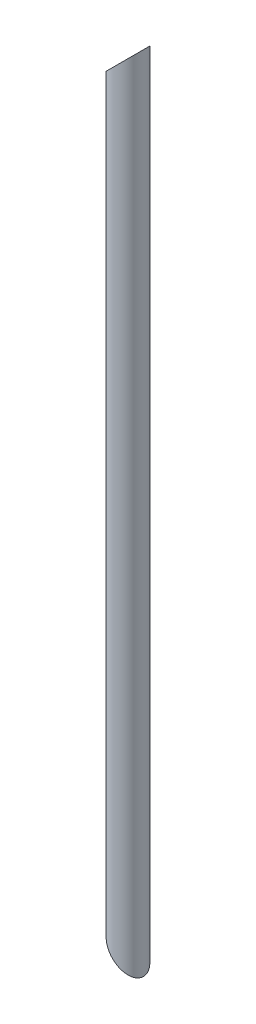
SolidWorks part; units mm, degrees
ref_plane "Plano frontal" through (0, 0, 0) normal (0, 0, 1) x (1, 0, 0)
ref_plane "Plano superior" through (0, 0, 0) normal (0, 1, 0) x (1, 0, 0)
ref_plane "Plano direito" through (0, 0, 0) normal (1, 0, 0) x (0, 0, -1)
sketch "Esboço2" plane through (0, 0, 0) normal (0, 0, 1) x (1, 0, 0)
  line L0 (0, 0) -> (0, 1650) construction
  line L1 (31.75, 0) -> (31.75, 1650)
  line L2 (31.75, 1650) -> (0, 1650)
  line L3 (31.75, 0) -> (0, 0)
  line L4 (0, 0) -> (0, 1650)
  dimension "D1" = 31.75
  dimension "D2" = 1650
revolve "Revolução2" add sketch "Esboço2" angle 360 about L0
sketch "Esboço3" plane through (0, 0, 0) normal (0, 0, 1) x (1, 0, 0)
  line L0 (-31.75, 1650) -> (31.75, 1650)
  line L1 (31.75, 1650) -> (-31.75, 1586.5)
  line L2 (-31.75, 1650) -> (-31.75, 0) construction
  line L3 (-31.75, 1586.5) -> (-31.75, 1650)
  line L4 (31.75, 0) -> (-31.75, 63.5)
  line L8 (-31.75, 63.5) -> (-31.75, 0)
  line L9 (-31.75, 0) -> (31.75, 0)
extrude "Corte-extrusão1" cut sketch "Esboço3" against normal through all both and the other way through all
sketch "Esboço9" plane through (0, 0, 0) normal (0, 1, 0) x (1, 0, 0)
  circle A0 centre (0, 0) radius 30.75
  dimension "D1" = 61.5
extrude "Corte-extrusão6" cut sketch "Esboço9" along normal through all
sketch "Esboço10" plane through (-809.125, 809.125, 0) normal (-0.7071, 0.7071, 0) x (0.7071, 0.7071, 0)
  line L0 (1189.1768, 0) -> (1099.3743, 0) construction
  ellipse E0 centre (1144.2755, 0) end of major axis (1099.3743, 0) minor radius 31.75 construction
